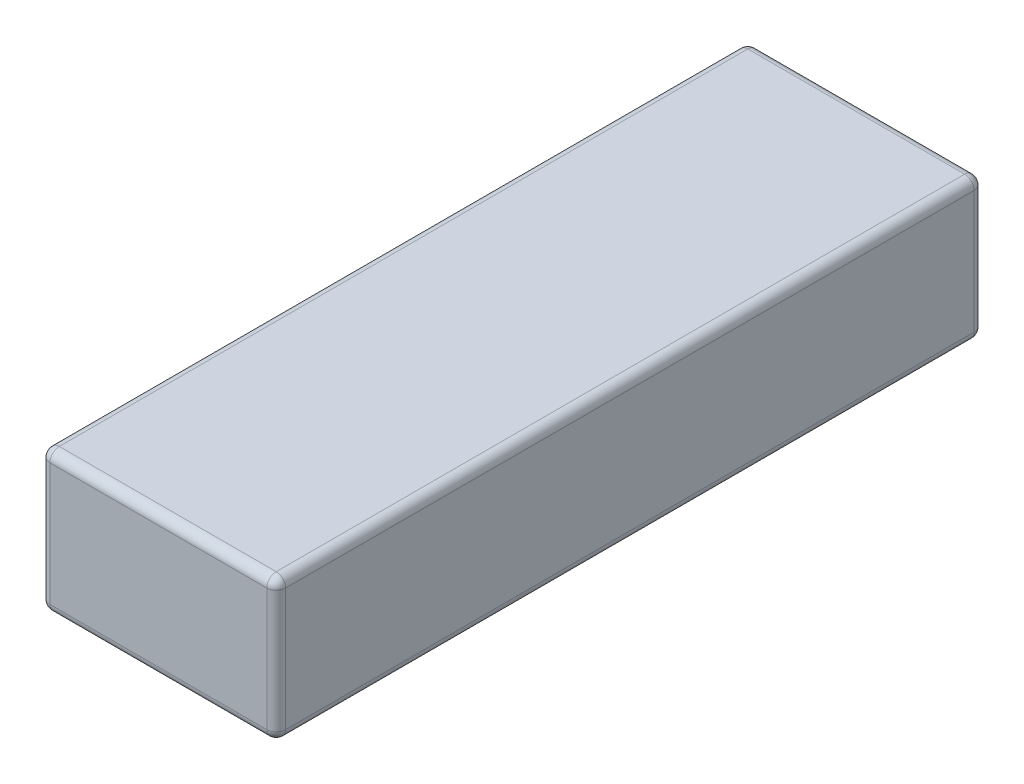
SolidWorks part; units mm, degrees
ref_plane "Front Plane" through (0, 0, 0) normal (0, 0, 1) x (1, 0, 0)
ref_plane "Top Plane" through (0, 0, 0) normal (0, 1, 0) x (1, 0, 0)
ref_plane "Right Plane" through (0, 0, 0) normal (1, 0, 0) x (0, 0, -1)
sketch "Sketch2" plane through (0, 0, 0) normal (0, 1, 0) x (1, 0, 0)
  line L1 (-25, 75) -> (25, 75)
  line L2 (-25, 75) -> (-25, -75)
  line L3 (-25, -75) -> (25, -75)
  line L4 (25, 75) -> (25, -75)
  line L5 (-25, 75) -> (25, -75) construction
  line L6 (-25, -75) -> (25, 75) construction
  point P0 (0, 0)
  dimension "D1" = 50
  dimension "D2" = 150
extrude "Boss-Extrude1" add sketch "Sketch2" along normal blind 30
fillet "Fillet1" radius 2 12 edges at (25, 0, 0) (25, 15, 75) (0, 0, 75) (25, 15, -75) (0, 0, -75) (0, 30, 75) (0, 30, -75) (25, 30, 0) (-25, 15, -75) (-25, 30, 0) (-25, 15, 75) (-25, 0, 0)
sketch "Sketch3" plane through (0, 0, -75) normal (0, 0, -1) x (-1, 0, 0)
  circle A0 centre (0, 15) radius 13
extrude "Cut-Extrude1" cut sketch "Sketch3" against normal blind 0.3
